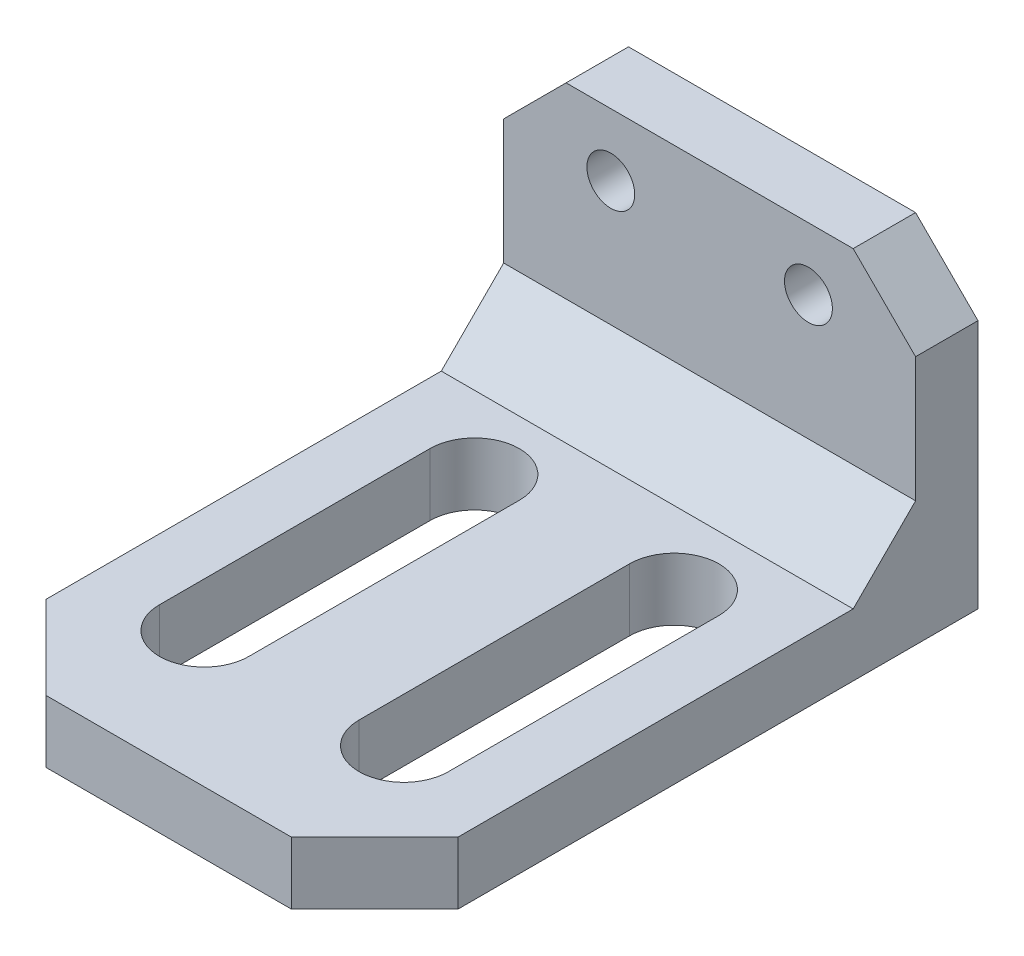
SolidWorks part; units mm, degrees
ref_plane "Front Plane" through (0, 0, 0) normal (0, 0, 1) x (1, 0, 0)
ref_plane "Top Plane" through (0, 0, 0) normal (0, 1, 0) x (1, 0, 0)
ref_plane "Right Plane" through (0, 0, 0) normal (1, 0, 0) x (0, 0, -1)
sketch "Sketch1" plane through (0, 0, 0) normal (0, 0, 1) x (1, 0, 0)
  line L0 (0, 13.7877) -> (0, -1.2123) construction
  line L1 (-9.9, -1.2123) -> (9.9, -1.2123)
  line L2 (-9.9, -1.2123) -> (-9.9, 13.7877)
  line L3 (-9.9, 13.7877) -> (9.9, 13.7877)
  line L4 (9.9, -1.2123) -> (9.9, 13.7877)
  circle A0 centre (-4.75, 10.7877) radius 1.15
  circle A1 centre (4.75, 10.7877) radius 1.15
  point P0 (0, 0)
  dimension "D3" = 2.3
  dimension "D1" = 19.8
  dimension "D2" = 15
  dimension "D4" = 4.75
  dimension "D5" = 12
extrude "Boss-Extrude1" add sketch "Sketch1" along normal blind 3
sketch "Sketch2" plane through (0, 0, 3) normal (0, 0, 1) x (1, 0, 0)
  line L0 (9.9, -1.2123) -> (9.9, 13.7877) construction
  line L1 (-9.9, -1.2123) -> (9.9, -1.2123)
  line L2 (-9.9, -1.2123) -> (-9.9, 1.7877)
  line L3 (-9.9, 1.7877) -> (9.9, 1.7877)
  line L4 (9.9, -1.2123) -> (9.9, 1.7877)
  dimension "D1" = 3
extrude "Boss-Extrude2" add sketch "Sketch2" along normal blind 26
chamfer "Chamfer1" distance 3 angle 45 3 edges at (9.9, 13.7877, 1.5) (-9.9, 13.7877, 1.5) (0, 1.7877, 3)
sketch "Sketch4" plane through (0, 1.7877, 0) normal (0, 1, 0) x (1, 0, 0)
  line L0 (0, -6) -> (0, -29) construction
  line L1 (9.9, -6) -> (-9.9, -6) construction
  line L2 (9.9, -29) -> (-9.9, -29) construction
  line L5 (4.7971, -13.9889) -> (4.7971, -22.5) construction
  line L6 (4.7971, -22.5) -> (4.7971, -9.5) construction
  line L7 (2.6471, -22.5) -> (2.6471, -9.5)
  line L8 (6.9471, -22.5) -> (6.9471, -9.5)
  line L9 (-4.7971, -13.9889) -> (-4.7971, -22.5) construction
  line L10 (-4.7971, -22.5) -> (-4.7971, -9.5) construction
  line L11 (-2.6471, -22.5) -> (-2.6471, -9.5)
  line L12 (-6.9471, -22.5) -> (-6.9471, -9.5)
  arc A2 (2.6471, -22.5) -> (6.9471, -22.5) centre (4.7971, -22.5) ccw
  arc A3 (6.9471, -9.5) -> (2.6471, -9.5) centre (4.7971, -9.5) ccw
  arc A4 (-2.6471, -22.5) -> (-6.9471, -22.5) centre (-4.7971, -22.5) cw
  arc A5 (-6.9471, -9.5) -> (-2.6471, -9.5) centre (-4.7971, -9.5) cw
  point P12 (4.7971, -16)
  point P21 (-4.7971, -16)
  dimension "D1" = 13
  dimension "D2" = 4.3
  dimension "D3" = 13
extrude "Cut-Extrude1" cut sketch "Sketch4" against normal blind 15
chamfer "Chamfer2" distance 4 angle 45 2 edges at (9.9, 0.2877, 29) (-9.9, 0.2877, 29)
